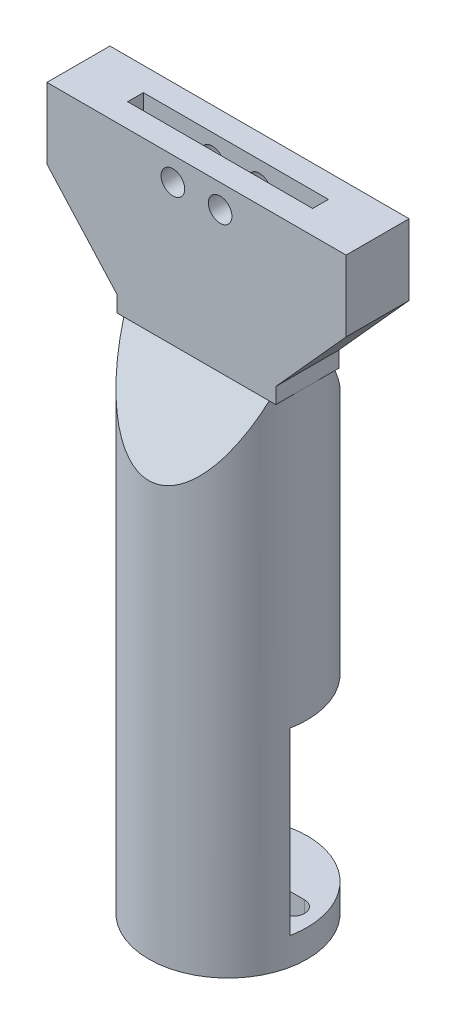
SolidWorks part; units mm, degrees
ref_plane "Front Plane" through (0, 0, 0) normal (0, 0, 1) x (1, 0, 0)
ref_plane "Top Plane" through (0, 0, 0) normal (0, 1, 0) x (1, 0, 0)
ref_plane "Right Plane" through (0, 0, 0) normal (1, 0, 0) x (0, 0, -1)
sketch "Sketch2" plane through (0, 0, 0) normal (0, 0, 1) x (1, 0, 0)
  line L0 (0, 0) -> (38, 0)
  line L1 (0, 0) -> (0, -9)
  line L2 (0, -9) -> (8.931, -18.9189)
  line L3 (8.931, -18.9189) -> (8.931, -20.9189)
  line L4 (38, 0) -> (38, -9)
  line L5 (19, 0) -> (19, -17.0648) construction
  line L6 (29.069, -18.9189) -> (29.069, -20.9189)
  line L7 (0, -18.9189) -> (35.4961, -18.9189) construction
  line L8 (38, -9) -> (29.069, -18.9189)
  line L9 (8.931, -20.9189) -> (29.069, -20.9189)
  dimension "D1" = 38
  dimension "D2" = 20.1379
  dimension "D3" = 9
  dimension "D4" = 48
  dimension "D5" = 2
extrude "Boss-Extrude1" add sketch "Sketch2" along normal blind 8
sketch "Sketch3" plane through (0, -20.9189, 0) normal (0, -1, 0) x (1, 0, 0)
  line L0 (8.931, 0) -> (29.069, 0) construction
  line L1 (19, 0) -> (19, 8) construction
  line L2 (8.931, 8) -> (29.069, 8) construction
  circle A0 centre (19, 4) radius 10.069
extrude "Boss-Extrude2" add sketch "Sketch3" along normal blind 63
sketch "Sketch4" plane through (0, 0, 0) normal (1, 0, 0) x (0, 0, -1)
  line L0 (0, -20.9189) -> (6.069, -31.2711)
  line L1 (6.069, -83.9189) -> (6.069, -20.9189) construction
  line L2 (6.069, -31.2711) -> (6.069, -20.9189)
  line L3 (6.069, -20.9189) -> (0, -20.9189) construction
  line L4 (6.069, -20.9189) -> (0, -20.9189)
  line L5 (-4, -20.9189) -> (-4, -34.3471) construction
  line L6 (-14.069, -20.9189) -> (-8, -20.9189)
  line L7 (-14.069, -31.2711) -> (-14.069, -20.9189)
  line L8 (-8, -20.9189) -> (-14.069, -31.2711)
  dimension "D1" = 12
extrude "Cut-Extrude1" cut sketch "Sketch4" along normal blind 83
sketch "Sketch7" plane through (0, 0, 0) normal (0, 0, -1) x (-1, 0, 0)
  line L0 (-38, 0) -> (0, 0) construction
  line L1 (0, 0) -> (0, -9) construction
  line L2 (-38, -9) -> (-38, 0) construction
  circle A0 centre (-22, -3) radius 1.5
  circle A1 centre (-16, -3) radius 1.5
  point P10 (0, 0)
  dimension "D1" = 3
  dimension "D2" = 3
  dimension "D3" = 6
  dimension "D4" = 3
  dimension "D5" = 16
  dimension "D6" = 16
extrude "Cut-Extrude2" cut sketch "Sketch7" against normal blind 10
ref_plane "Plane1" through (0, 0, 4) normal (0, 0, -1) x (-1, 0, 0)
sketch "Sketch9" plane through (0, 0, 0) normal (0, 1, 0) x (1, 0, 0)
  line L0 (38, 0) -> (0, 0) construction
  line L1 (7.25, -3) -> (30.75, -3)
  line L2 (7.25, -3) -> (7.25, -5)
  line L3 (7.25, -5) -> (30.75, -5)
  line L4 (30.75, -3) -> (30.75, -5)
  line L8 (0, -8) -> (0, 0) construction
  dimension "D1" = 2
  dimension "D2" = 23.5
  dimension "D3" = 3
  dimension "D4" = 7.25
extrude "Cut-Extrude3" cut sketch "Sketch9" against normal blind 8
sketch "Sketch10" plane through (0, 0, 0) normal (1, 0, 0) x (0, 0, -1)
  line L0 (6.069, -80.4189) -> (-6.0179, -80.4189)
  line L1 (6.069, -83.9189) -> (6.069, -31.2711) construction
  line L2 (-6.0179, -80.4189) -> (-6.0179, -57.595)
  line L3 (-6.0179, -57.595) -> (6.069, -57.595)
  line L4 (6.069, -57.595) -> (6.069, -80.4189)
  line L5 (-14.069, -83.9189) -> (6.069, -83.9189) construction
  line L6 (-14.0179, -83.9189) -> (-14.0179, -61.3484) construction
  dimension "D1" = 3.5
  dimension "D2" = 8
extrude "Cut-Extrude4" cut sketch "Sketch10" along normal blind 48
sketch "Sketch12" plane through (0, -83.9189, 0) normal (0, -1, 0) x (1, 0, 0)
  line L0 (12.6239, 2.6428) -> (25.8645, 2.6428) construction
  line L1 (12.6239, 4.1428) -> (25.8645, 4.1428)
  line L2 (12.6239, 1.1428) -> (25.8645, 1.1428)
  arc A0 (12.6239, 4.1428) -> (12.6239, 1.1428) centre (12.6239, 2.6428) ccw
  arc A1 (25.8645, 1.1428) -> (25.8645, 4.1428) centre (25.8645, 2.6428) ccw
  point P2 (19.2442, 2.6428)
  point P7 (19.2105, 2.9852)
  point P8 (19.2442, 2.6428)
  dimension "D1" = 1.5
extrude "Cut-Extrude5" cut sketch "Sketch12" against normal blind 14
